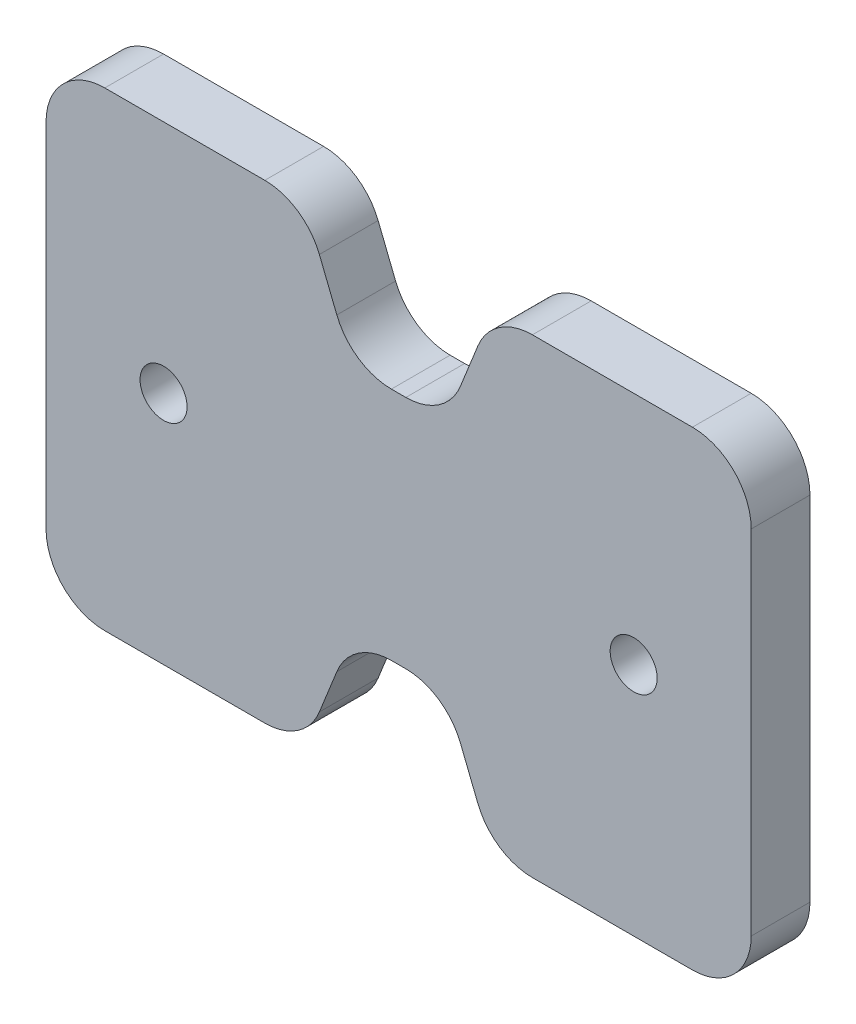
SolidWorks part; units mm, degrees
ref_plane "Plan de face" through (0, 0, 0) normal (0, 0, 1) x (1, 0, 0)
ref_plane "Plan de dessus" through (0, 0, 0) normal (0, 1, 0) x (1, 0, 0)
ref_plane "Plan de droite" through (0, 0, 0) normal (1, 0, 0) x (0, 0, -1)
sketch "Esquisse1" plane through (0, 0, 0) normal (0, 0, 1) x (1, 0, 0)
  line L0 (-30, 20) -> (-30, -20)
  line L1 (-30, -20) -> (-8, -20)
  line L2 (-8, -20) -> (-4, -10)
  line L3 (-4, -10) -> (4, -10)
  line L4 (4, -10) -> (8, -20)
  line L5 (8, -20) -> (30, -20)
  line L6 (30, -20) -> (30, 20)
  line L7 (30, 20) -> (8, 20)
  line L8 (8, 20) -> (4, 10)
  line L9 (4, 10) -> (-4, 10)
  line L10 (-4, 10) -> (-8, 20)
  line L11 (-8, 20) -> (-30, 20)
  line L12 (0, 0) -> (0, 18.6782) construction
  line L13 (0, 0) -> (30, 0) construction
  circle A0 centre (20, 0) radius 2
  circle A1 centre (-20, 0) radius 2
  point P18 (0, 0)
  point P19 (19.3458, 0)
  dimension "D6" = 4
  dimension "D1" = 60
  dimension "D2" = 40
  dimension "D3" = 20
  dimension "D4" = 8
  dimension "D5" = 16
  dimension "D7" = 40
extrude "Boss.-Extru.1" add sketch "Esquisse1" along normal blind 5
fillet "Congé1" radius 5 12 edges at (30, -20, 2.5) (8, -20, 2.5) (-30, -20, 2.5) (-8, -20, 2.5) (-4, -10, 2.5) (4, -10, 2.5) (8, 20, 2.5) (4, 10, 2.5) (-4, 10, 2.5) (-8, 20, 2.5) (-30, 20, 2.5) (30, 20, 2.5)
